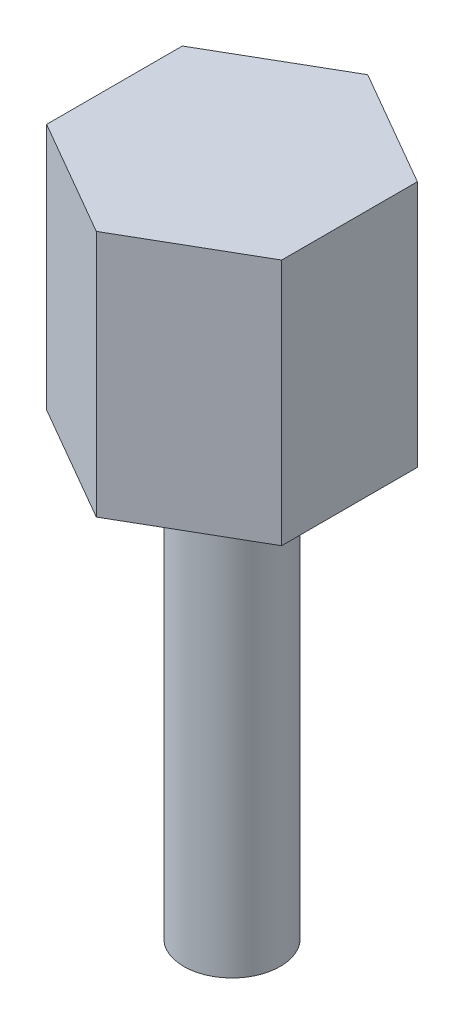
SolidWorks part; units mm, degrees
ref_plane "Front Plane" through (0, 0, 0) normal (0, 0, 1) x (1, 0, 0)
ref_plane "Top Plane" through (0, 0, 0) normal (0, 1, 0) x (1, 0, 0)
ref_plane "Right Plane" through (0, 0, 0) normal (1, 0, 0) x (0, 0, -1)
sketch "Sketch2" plane through (0, 0, 0) normal (0, 1, 0) x (1, 0, 0)
  circle A0 centre (0, 0) radius 0.78
  dimension "D1" = 1.56
extrude "Boss-Extrude1" add sketch "Sketch2" along normal blind 7
sketch "Sketch3" plane through (0, 7, 0) normal (0, 1, 0) x (1, 0, 0)
  line L0 (0, 0) -> (1.9, 0) construction
  line L1 (1.9, 1.097) -> (0, 2.1939)
  line L2 (0, 2.1939) -> (-1.9, 1.097)
  line L3 (-1.9, 1.097) -> (-1.9, -1.097)
  line L4 (-1.9, -1.097) -> (0, -2.1939)
  line L5 (0, -2.1939) -> (1.9, -1.097)
  line L6 (1.9, -1.097) -> (1.9, 1.097)
  circle A0 centre (0, 0) radius 1.9 construction
  dimension "D1" = 3.8
extrude "Boss-Extrude2" add sketch "Sketch3" along normal blind 4
